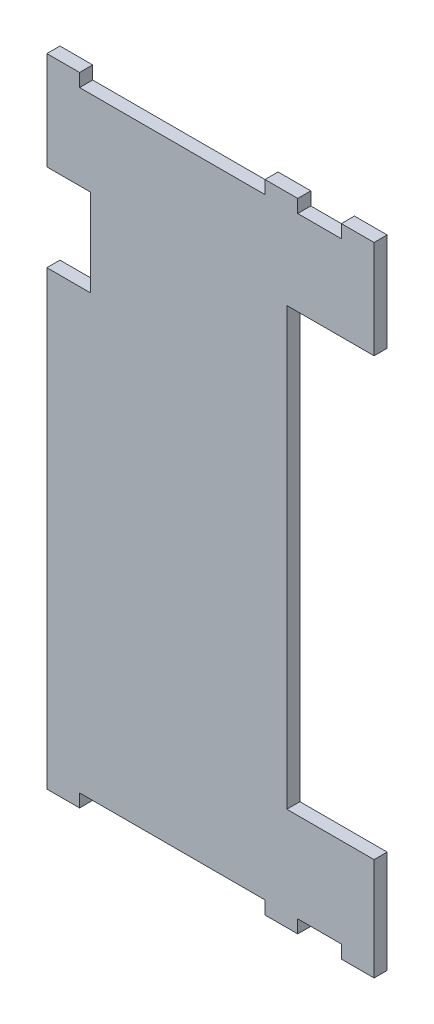
SolidWorks part; units mm, degrees
ref_plane "Plano frontal" through (0, 0, 0) normal (0, 0, 1) x (1, 0, 0)
ref_plane "Plano superior" through (0, 0, 0) normal (0, 1, 0) x (1, 0, 0)
ref_plane "Plano direito" through (0, 0, 0) normal (1, 0, 0) x (0, 0, -1)
sketch "Esboço1" plane through (0, 0, 0) normal (0, 0, 1) x (1, 0, 0)
  line L1 (0, 0) -> (150, 0)
  line L2 (0, 0) -> (0, 292)
  line L3 (0, 292) -> (150, 292)
  line L4 (150, 0) -> (150, 292)
extrude "Ressalto-extrusão1" add sketch "Esboço1" along normal blind 6
sketch "Esboço2" plane through (0, 0, 0) normal (0, 0, -1) x (-1, 0, 0)
  line L0 (-130.3601, 0) -> (-130.3601, 46) construction
  line L1 (0, 0) -> (-150, 0) construction
  line L2 (-133.97, 292) -> (-133.97, 246) construction
  line L3 (-150, 292) -> (0, 292) construction
  line L4 (-150, 0) -> (-150, 292) construction
  line L5 (-150, 247) -> (-110, 247)
  line L6 (-150, 247) -> (-150, 47)
  line L7 (-150, 47) -> (-110, 47)
  line L8 (-110, 247) -> (-110, 47)
extrude "Corte-extrusão1" cut sketch "Esboço2" against normal through all
sketch "Esboço5" plane through (0, 0, 0) normal (0, 0, -1) x (-1, 0, 0)
  line L0 (-150, 290.5586) -> (-135, 290.5586) construction
  line L1 (-150, 247) -> (-150, 292) construction
  line L2 (-150, 292) -> (0, 292) construction
  line L3 (-135, 292) -> (-115, 292)
  line L4 (-135, 292) -> (-135, 286)
  line L5 (-135, 286) -> (-115, 286)
  line L6 (-115, 292) -> (-115, 286)
  line L7 (-115, 288.1251) -> (-100, 288.1251) construction
  line L8 (0, 288.1251) -> (-15, 288.1251) construction
  line L9 (0, 292) -> (0, 0) construction
  line L10 (-150, 3.2132) -> (-135, 3.2132) construction
  line L11 (-100, 292) -> (-15, 292)
  line L12 (-100, 292) -> (-100, 286)
  line L13 (-100, 286) -> (-15, 286)
  line L14 (-15, 292) -> (-15, 286)
  line L15 (-150, 0) -> (-150, 47) construction
  line L16 (0, 0) -> (-150, 0) construction
  line L17 (-135, 0) -> (-115, 0)
  line L18 (-135, 0) -> (-135, 6)
  line L19 (-135, 6) -> (-115, 6)
  line L20 (-115, 0) -> (-115, 6)
  line L21 (-115, 2.5335) -> (-100, 2.5335) construction
  line L22 (0, 2.5335) -> (-15, 2.5335) construction
  line L24 (-100, 0) -> (-15, 0)
  line L25 (-100, 0) -> (-100, 6)
  line L26 (-100, 6) -> (-15, 6)
  line L27 (-15, 0) -> (-15, 6)
extrude "Corte-extrusão2" cut sketch "Esboço5" against normal through all
sketch "Esboço7" plane through (0, 0, 0) normal (0, 0, -1) x (-1, 0, 0)
  line L0 (-110, 247) -> (-20, 247) construction
  line L1 (0, 292) -> (0, 0) construction
  line L2 (0, 247) -> (-20, 247)
  line L3 (0, 247) -> (0, 207)
  line L4 (0, 207) -> (-20, 207)
  line L5 (-20, 247) -> (-20, 207)
extrude "Corte-extrusão3" cut sketch "Esboço7" against normal through all
